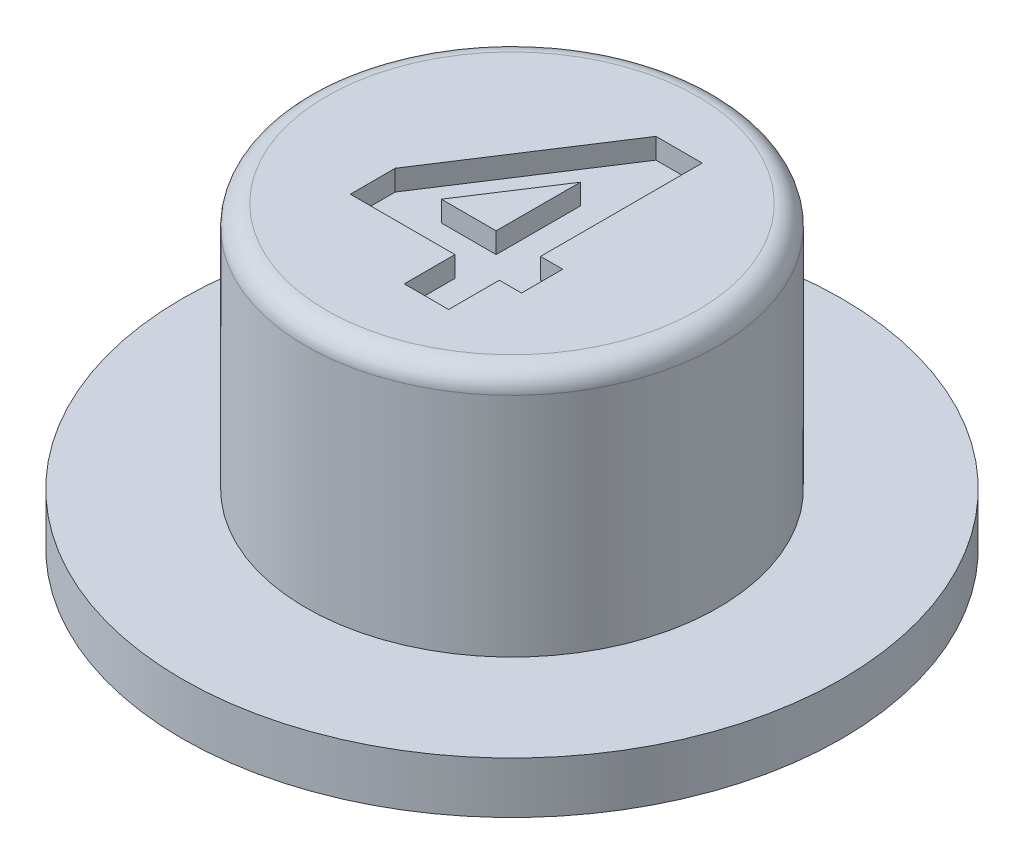
SolidWorks part; units mm, degrees
ref_plane "Front Plane" through (0, 0, 0) normal (0, 0, 1) x (1, 0, 0)
ref_plane "Top Plane" through (0, 0, 0) normal (0, 1, 0) x (1, 0, 0)
ref_plane "Right Plane" through (0, 0, 0) normal (1, 0, 0) x (0, 0, -1)
sketch "Sketch1" plane through (0, 0, 0) normal (0, 0, 1) x (1, 0, 0)
  line L1 (0, 7.25) -> (5, 7.25)
  line L2 (5, 7.25) -> (5, 1.25)
  line L3 (5, 1.25) -> (8, 1.25)
  line L4 (8, 1.25) -> (8, 0)
  line L6 (0, 7.25) -> (0, 6.9292) construction
  line L7 (0, 7.25) -> (0, 0)
  line L10 (0, 0) -> (8, 0)
  dimension "D1" = 5
  dimension "D2" = 3
  dimension "D3" = 6
  dimension "D4" = 1.25
revolve "Revolve1" add sketch "Sketch1" angle 360 about L6
sketch "Sketch2" plane through (0, 0, 0) normal (0, -1, 0) x (1, 0, 0)
  line L1 (-1.25, -1.75) -> (1.25, -1.75)
  line L2 (-1.25, -1.75) -> (-1.25, 1.75)
  line L3 (-1.25, 1.75) -> (1.25, 1.75)
  line L4 (1.25, -1.75) -> (1.25, 1.75)
  line L5 (-1.25, -1.75) -> (1.25, 1.75) construction
  line L6 (-1.25, 1.75) -> (1.25, -1.75) construction
  point P0 (0, 0)
  dimension "D1" = 2.5
  dimension "D2" = 3.5
extrude "Cut-Extrude1" cut sketch "Sketch2" against normal blind 3.5 contours L3 L4 L1 L2
fillet "Fillet1" radius 0.5 1 edges at (-5, 7.25, 0)
sketch "Sketch3" plane through (0, 7.25, 0) normal (0, 1, 0) x (1, 0, 0)
  line L0 (-3.3541, -3) -> (3.3541, -3) construction
  line L1 (0, 0) -> (0, -3) construction
  circle A0 centre (0, 0) radius 4.5 construction
  text T0 "4\r\n" font "Century Gothic" height 6
  dimension "D1" = 3
extrude "Cut-Extrude2" cut sketch "Sketch3" against normal blind 0.5
